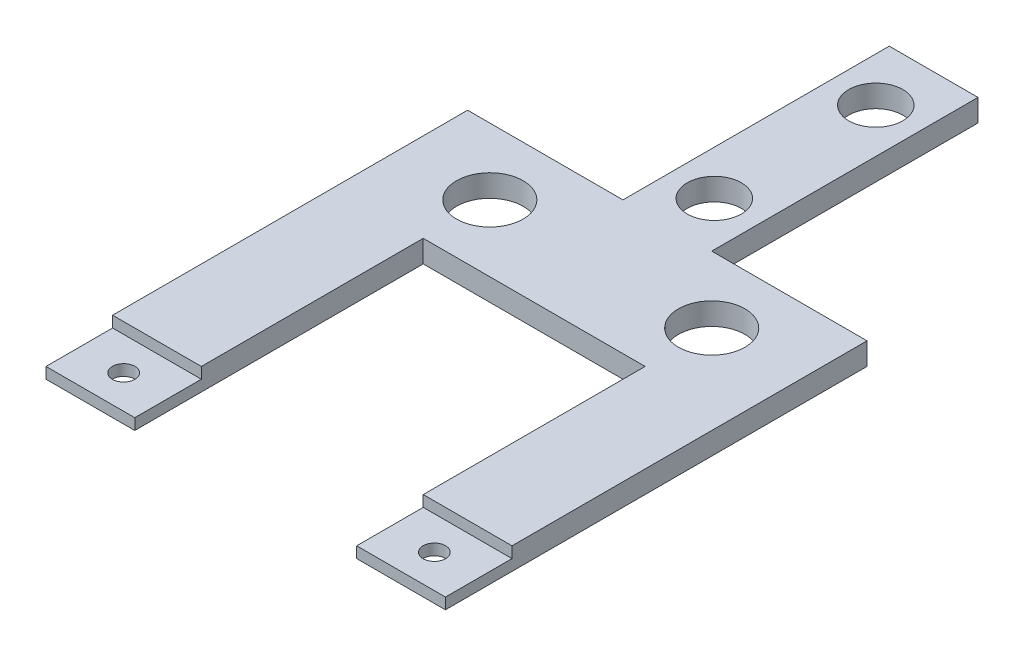
SolidWorks part; units mm, degrees
ref_plane "Front Plane" through (0, 0, 0) normal (0, 0, 1) x (1, 0, 0)
ref_plane "Top Plane" through (0, 0, 0) normal (0, 1, 0) x (1, 0, 0)
ref_plane "Right Plane" through (0, 0, 0) normal (1, 0, 0) x (0, 0, -1)
sketch "Sketch1" plane through (0, 0, 0) normal (0, 1, 0) x (1, 0, 0)
  line L1 (-14.2875, 15.0812) -> (14.2875, 15.0812)
  line L2 (-14.2875, 15.0812) -> (-14.2875, -15.0813)
  line L3 (-14.2875, -15.0813) -> (14.2875, -15.0812)
  line L4 (14.2875, 15.0812) -> (14.2875, -15.0812)
  line L5 (-7.9375, -15.0813) -> (7.9375, -15.0813)
  line L6 (-7.9375, -15.0813) -> (-7.9375, 5.5563)
  line L7 (-7.9375, 5.5563) -> (7.9375, 5.5563)
  line L8 (7.9375, -15.0813) -> (7.9375, 5.5563)
  line L9 (-3.175, 15.0813) -> (3.175, 15.0813)
  line L10 (-3.175, 15.0813) -> (-3.175, 34.1313)
  line L11 (-3.175, 34.1313) -> (3.175, 34.1313)
  line L12 (3.175, 15.0813) -> (3.175, 34.1313)
  point P4 (0, 15.0813)
  point P6 (-14.2875, 0)
  point P11 (0, 5.5563)
  point P16 (0, 15.0813)
  dimension "D1" = 28.575
  dimension "D2" = 30.1625
  dimension "D3" = 6.35
  dimension "D4" = 9.525
  dimension "D5" = 6.35
  dimension "D6" = 19.05
extrude "Boss-Extrude1" add sketch "Sketch1" along normal mid plane 1.5875 contours L8 L3 L4 L1 L2 L6 L7 | L10 L9 L12 L11
sketch "Sketch2" plane through (0, 0.7937, 0) normal (0, 1, 0) x (1, 0, 0)
  line L0 (-7.9375, -15.0813) -> (-7.9375, 5.5563) construction
  line L1 (-14.2875, -15.0813) -> (-7.9375, -15.0813)
  line L2 (-14.2875, -15.0813) -> (-14.2875, -10.3188)
  line L3 (-14.2875, -10.3188) -> (-7.9375, -10.3188)
  line L4 (-7.9375, -15.0813) -> (-7.9375, -10.3188)
  line L5 (14.2875, 15.0812) -> (14.2875, -15.0812) construction
  line L6 (7.9375, -15.0812) -> (14.2875, -15.0812)
  line L7 (7.9375, -15.0812) -> (7.9375, -10.3188)
  line L8 (7.9375, -10.3188) -> (14.2875, -10.3188)
  line L9 (14.2875, -15.0812) -> (14.2875, -10.3188)
  dimension "D1" = 4.7625
extrude "Cut-Extrude1" cut sketch "Sketch2" against normal blind 0.7937
sketch "Sketch3" plane through (0, 0.7937, 0) normal (0, 1, 0) x (1, 0, 0)
  line L0 (-7.9375, -10.3188) -> (-14.2875, -10.3188) construction
  line L1 (-14.2875, -10.3188) -> (-14.2875, -15.0813) construction
  line L2 (0, -1000) -> (0, 49000) construction
  line L3 (-14.2875, 15.0812) -> (-14.2875, -10.3188) construction
  line L4 (-14.2875, 15.0812) -> (-3.175, 15.0812) construction
  line L5 (-3.175, 34.1313) -> (3.175, 34.1313) construction
  circle A0 centre (-11.1125, -12.7) radius 0.8065
  circle A1 centre (-7.9375, 10.3187) radius 2.3813
  circle A2 centre (11.1125, -12.7) radius 0.8065
  circle A3 centre (7.9375, 10.3187) radius 2.3813
  circle A4 centre (0, 18.442) radius 1.9364
  circle A5 centre (0, 29.994) radius 1.9364
  point P6 (-11.1125, -10.3188)
  point P9 (-14.2875, -12.7)
  dimension "D1" = 1.6129
  dimension "D2" = 4.7625
  dimension "D3" = 6.35
  dimension "D4" = 4.7625
  dimension "D5" = 11.552
  dimension "D6" = 4.1372
  dimension "D7" = 3.8728
extrude "Cut-Extrude2" cut sketch "Sketch3" against normal up to surface (1.5875 mm away) from surface at 0 up to face at (0, -0.7937, -6.6146) starting at face at (0, 0.7937, -8.2021)
